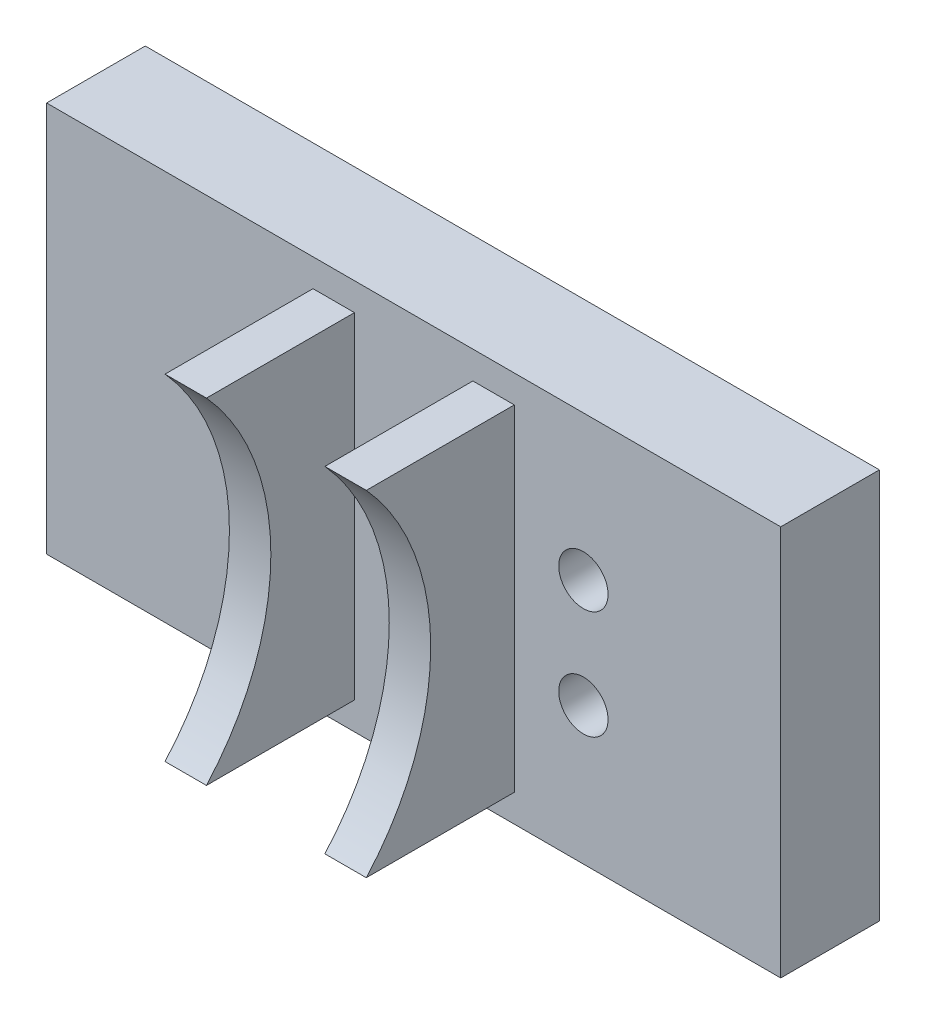
SolidWorks part; units mm, degrees
ref_plane "Front Plane" through (0, 0, 0) normal (0, 0, 1) x (1, 0, 0)
ref_plane "Top Plane" through (0, 0, 0) normal (0, 1, 0) x (1, 0, 0)
ref_plane "Right Plane" through (0, 0, 0) normal (1, 0, 0) x (0, 0, -1)
sketch "Sketch1" plane through (0, 0, 0) normal (0, 0, 1) x (1, 0, 0)
  line L1 (-22.5913, 13.9973) -> (-96.9913, 13.9973)
  line L2 (-22.5913, 13.9973) -> (-22.5913, -25.6027)
  line L3 (-22.5913, -25.6027) -> (-96.9913, -25.6027)
  line L4 (-96.9913, 13.9973) -> (-96.9913, -25.6027)
  dimension "D1" = 74.4
  dimension "D2" = 39.6
extrude "Boss-Extrude4" add sketch "Sketch1" along normal blind 10
sketch "Sketch4" plane through (0, 0, 10) normal (0, 0, 1) x (1, 0, 0)
  line L0 (-96.9913, 13.9973) -> (-96.9913, -25.6027) construction
  line L1 (-69.9913, -22.8027) -> (-65.7913, -22.8027)
  line L2 (-69.9913, -22.8027) -> (-69.9913, 11.1973)
  line L3 (-69.9913, 11.1973) -> (-65.7913, 11.1973)
  line L4 (-65.7913, -22.8027) -> (-65.7913, 11.1973)
  line L5 (-49.5913, 11.1973) -> (-53.7913, 11.1973)
  line L6 (-49.5913, 11.1973) -> (-49.5913, -22.8027)
  line L7 (-49.5913, -22.8027) -> (-53.7913, -22.8027)
  line L8 (-53.7913, 11.1973) -> (-53.7913, -22.8027)
  line L10 (-22.5913, -25.6027) -> (-22.5913, 13.9973) construction
  line L11 (-22.5913, 13.9973) -> (-96.9913, 13.9973) construction
  dimension "D1" = 34
  dimension "D2" = 34
  dimension "D3" = 4.2
  dimension "D4" = 4.2
  dimension "D5" = 12
  dimension "D6" = 27
  dimension "D7" = 27
  dimension "D8" = 2.8
  dimension "D9" = 2.8
extrude "Boss-Extrude7" add sketch "Sketch4" along normal blind 15
sketch "Sketch5" plane through (-49.5913, 0, 0) normal (1, 0, 0) x (0, 0, -1)
  arc A0 (-25, 11.1973) -> (-25, -22.8027) centre (-43.8722, -5.8027) cw
  dimension "D1" = 25.4
extrude "Cut-Extrude6" cut sketch "Sketch5" against normal blind 8 and the other way through all flip side to cut
sketch "Sketch6" plane through (-65.7913, 0, 0) normal (1, 0, 0) x (0, 0, -1)
  arc A0 (-25, -22.8027) -> (-25, 11.1973) centre (-43.8722, -5.8027) ccw
  dimension "D1" = 25.4
extrude "Cut-Extrude12" cut sketch "Sketch6" against normal blind 15 and the other way through all
sketch "Sketch7" plane through (0, 0, 10) normal (0, 0, 1) x (1, 0, 0)
  line L0 (-22.5913, -25.6027) -> (-22.5913, 13.9973) construction
  line L1 (-22.5913, 13.9973) -> (-96.9913, 13.9973) construction
  circle A0 centre (-42.5913, -11.6827) radius 2.5
  circle A1 centre (-42.5913, -0.6827) radius 2.5
  circle A2 centre (-76.0087, -0.6827) radius 2.5
  circle A3 centre (-76.0087, -11.6827) radius 2.5
  point P10 (0, 0)
  point P13 (0, 0)
  dimension "D1" = 5
  dimension "D2" = 20
  dimension "D3" = 11
  dimension "D4" = 14.68
other "AlignGroup1"
extrude "Cut-Extrude13" cut sketch "Sketch7" against normal blind 15
